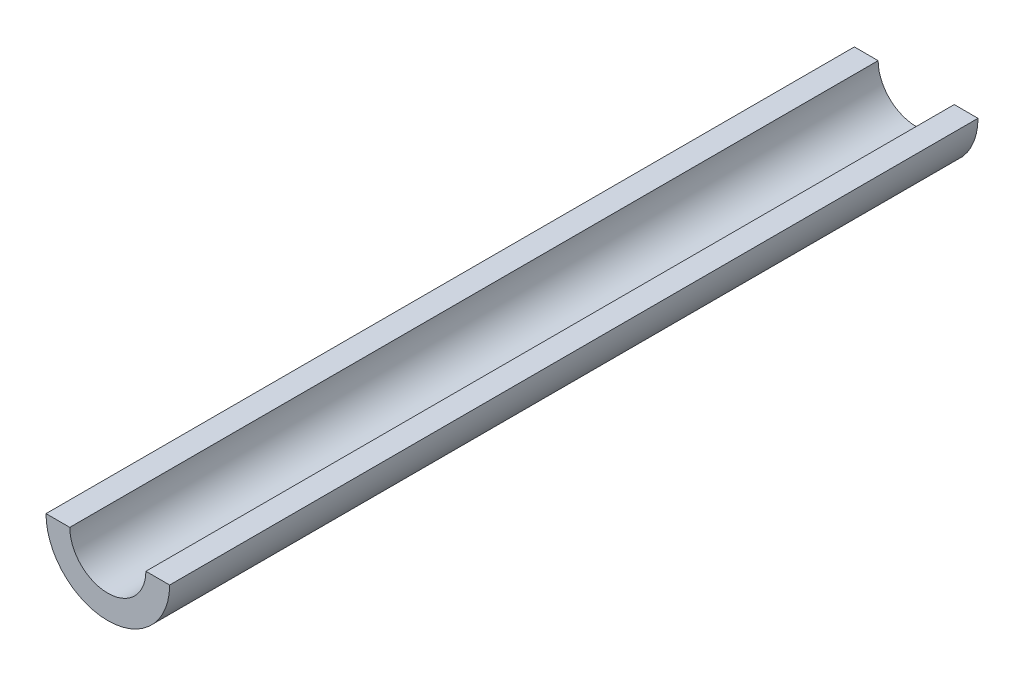
SolidWorks part; units mm, degrees
ref_plane "Front Plane" through (0, 0, 0) normal (0, 0, 1) x (1, 0, 0)
ref_plane "Top Plane" through (0, 0, 0) normal (0, 1, 0) x (1, 0, 0)
ref_plane "Right Plane" through (0, 0, 0) normal (1, 0, 0) x (0, 0, -1)
sketch "Sketch2" plane through (0, 0, 0) normal (0, 0, 1) x (1, 0, 0)
  line L0 (-13, 0) -> (-8, 0)
  line L1 (8, 0) -> (13, 0)
  arc A0 (-8, 0) -> (8, 0) centre (0, 0) ccw
  arc A1 (-13, 0) -> (13, 0) centre (0, 0) ccw
  circle A3 centre (0, 0) radius 8 construction
  circle A4 centre (0, 0) radius 13 construction
  point P1 (13, 0)
  point P7 (7.6504, 2.339)
  dimension "D1" = 16
  dimension "D2" = 5
extrude "Boss-Extrude1" add sketch "Sketch2" along normal blind 170
